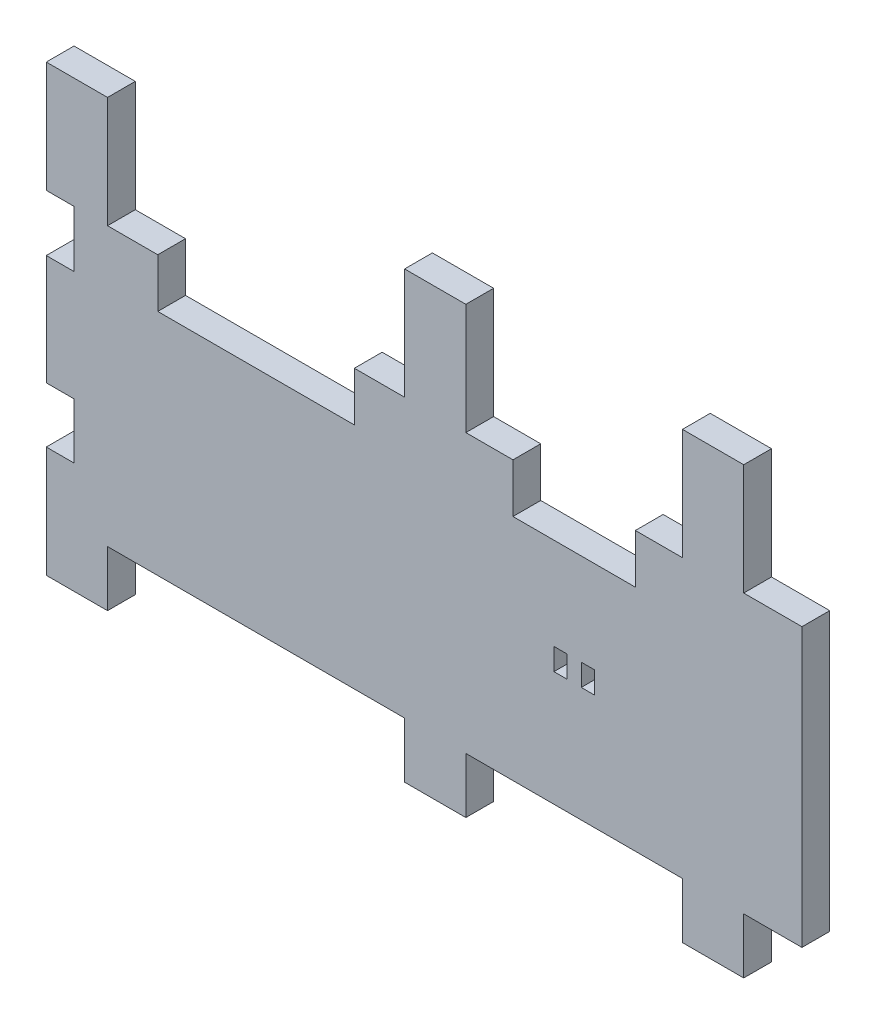
SolidWorks part; units mm, degrees
ref_plane "Front Plane" through (0, 0, 0) normal (0, 0, 1) x (1, 0, 0)
ref_plane "Top Plane" through (0, 0, 0) normal (0, 1, 0) x (1, 0, 0)
ref_plane "Right Plane" through (0, 0, 0) normal (1, 0, 0) x (0, 0, -1)
sketch "Sketch2" plane through (0, 0, 0) normal (0, 0, 1) x (1, 0, 0)
  line L1 (-88.9, -50.8) -> (88.9, -50.8)
  line L2 (-88.9, -50.8) -> (-88.9, 50.8)
  line L3 (-88.9, 50.8) -> (88.9, 50.8)
  line L4 (88.9, -50.8) -> (88.9, 50.8)
  line L5 (-88.9, -50.8) -> (88.9, 50.8) construction
  line L6 (-88.9, 50.8) -> (88.9, -50.8) construction
  point P0 (0, 0)
  dimension "D1" = 101.6
  dimension "D2" = 177.8
extrude "Boss-Extrude3" add sketch "Sketch2" along normal blind 6.35
sketch "Sketch3" plane through (0, 0, 6.35) normal (0, 0, 1) x (1, 0, 0)
  line L0 (-88.9, 50.8) -> (-82.55, 50.8)
  line L1 (-88.9, 50.8) -> (-88.9, 35.56)
  line L2 (-88.9, -50.8) -> (88.9, -50.8) construction
  line L3 (-88.9, 50.8) -> (-74.9, 50.8)
  line L4 (88.9, 50.8) -> (-88.9, 50.8) construction
  line L5 (-82.55, 50.8) -> (-76.2, 50.8)
  line L6 (-14.65, 50.8) -> (-0.65, 50.8)
  line L7 (-88.9, 50.8) -> (-88.9, 35.56)
  line L8 (-7, 50.8) -> (5.3812, 50.8)
  line L9 (-82.55, 0) -> (-82.55, 12.5042)
  line L10 (-88.9, 50.8) -> (-88.9, -50.8) construction
  line L11 (-7, 50.8) -> (-7, 25.4)
  line L12 (-88.9, 50.8) -> (-88.9, 25.4) construction
  line L13 (-82.55, 25.4) -> (-82.55, 12.5042)
  line L14 (-82.55, 25.4) -> (-74.9, 25.4)
  line L15 (56.509, 25.4) -> (56.509, 50.8)
  line L16 (56.509, 25.4) -> (70.509, 25.4)
  line L17 (56.509, 50.8) -> (70.509, 50.8)
  line L18 (70.509, 25.4) -> (70.509, 50.8)
  line L19 (70.509, 25.4) -> (88.9, 25.4) construction
  line L20 (-82.55, 50.8) -> (-14.65, 50.8) construction
  line L21 (-0.65, 50.8) -> (56.509, 50.8) construction
  line L22 (70.509, 50.8) -> (88.9, 50.8) construction
  line L23 (70.509, -50.8) -> (88.9, -50.8) construction
  line L24 (-74.9, 50.8) -> (-74.9, 25.4)
  line L25 (-88.9, -38.1) -> (-74.9, -38.1)
  line L26 (-82.55, 50.8) -> (-14.65, 50.8)
  line L27 (-88.9, -38.1) -> (-88.9, -50.8)
  line L28 (-88.9, -50.8) -> (-74.9, -50.8)
  line L29 (-74.9, -38.1) -> (-74.9, -50.8)
  line L30 (-7, -50.8) -> (-7, -38.1)
  line L31 (70.509, 50.8) -> (70.509, 25.4)
  line L32 (70.509, 25.4) -> (88.9, 25.4)
  line L33 (70.509, 25.4) -> (70.509, 50.8)
  line L34 (70.509, 50.8) -> (88.9, 50.8)
  line L35 (88.9, 25.4) -> (88.9, 50.8)
  line L36 (7, -50.8) -> (7, -38.1)
  line L37 (-0.65, -50.8) -> (7, -50.8)
  line L38 (70.509, -38.1) -> (88.9, -38.1) construction
  line L39 (-7, -38.1) -> (7, -38.1)
  line L40 (-7, -50.8) -> (-7, -38.1)
  line L41 (88.9, -38.1) -> (88.9, -50.8)
  line L42 (70.509, -50.8) -> (88.9, -50.8)
  line L43 (70.509, -38.1) -> (70.509, -50.8)
  line L44 (70.509, -38.1) -> (88.9, -38.1)
  line L45 (70.509, -50.8) -> (70.509, -38.1)
  line L46 (-7, -50.8) -> (5.3812, -50.8)
  line L47 (-88.9, -44.45) -> (-88.9, -25.4) construction
  line L48 (-7, 50.8) -> (7, 50.8)
  line L49 (-7, 50.8) -> (-7, 25.4)
  line L50 (-7, 25.4) -> (7, 25.4)
  line L51 (7, 50.8) -> (7, 25.4)
  line L52 (-7, -38.1) -> (7, -38.1)
  line L53 (70.509, -38.1) -> (70.509, -50.8)
  line L54 (56.509, -50.8) -> (70.509, -50.8)
  line L55 (56.509, -38.1) -> (70.509, -38.1)
  line L56 (56.509, -38.1) -> (56.509, -50.8)
  line L57 (-7, -38.1) -> (-7, -50.8)
  line L58 (-7, -50.8) -> (7, -50.8)
  line L59 (7, -38.1) -> (7, -50.8)
  line L60 (-74.9, -38.1) -> (-7, -38.1)
  line L61 (-74.9, -38.1) -> (-74.9, -50.8)
  line L62 (-74.9, -50.8) -> (-7, -50.8)
  line L63 (-88.9, -50.8) -> (-88.9, -38.1)
  line L64 (-88.9, -50.8) -> (-82.55, -50.8)
  line L65 (-7, -38.1) -> (-7, -50.8)
  line L66 (7, -38.1) -> (56.509, -38.1)
  line L67 (-82.55, 25.4) -> (-82.55, 50.8)
  line L68 (7, -38.1) -> (7, -50.8)
  line L69 (-88.9, 35.56) -> (-88.9, -38.1)
  line L70 (7, -50.8) -> (56.509, -50.8)
  line L72 (-88.9, 38.1) -> (-88.9, 25.4)
  line L75 (-88.9, -25.4) -> (88.9, -25.4) construction
  line L76 (-88.9, 25.4) -> (-82.55, 25.4)
  line L78 (56.509, -38.1) -> (56.509, -50.8)
  line L80 (-88.9, 35.56) -> (-88.9, 25.4)
  line L81 (-88.9, 25.4) -> (-82.55, 25.4)
  line L83 (-88.9, -38.1) -> (-88.9, -25.4)
  line L84 (-88.9, -25.4) -> (-82.4404, -25.4)
  line L85 (-82.4404, -38.1) -> (-82.4404, -25.4)
  line L86 (-82.55, 50.8) -> (-76.2, 50.8)
  line L87 (56.509, 25.4) -> (7, 25.4)
  line L88 (56.509, 25.4) -> (56.509, 50.8)
  line L90 (-88.9, 12.5042) -> (-82.55, 12.5042) construction
  line L91 (-85.725, -12.7) -> (-82.4404, -12.7) construction
  line L92 (-82.4404, -12.7) -> (-88.9, -12.7) construction
  line L93 (-82.55, 50.8) -> (-76.2, 50.8)
  line L94 (-0.65, 50.8) -> (7, 50.8)
  line L95 (56.509, 50.8) -> (7, 50.8)
  line L96 (7, 25.4) -> (7, 50.8)
  line L97 (7, 50.8) -> (7, 25.4)
  line L98 (-88.9, -34.925) -> (-82.55, -34.925) construction
  line L99 (-14.65, 50.8) -> (-7, 50.8)
  line L100 (-74.9, 50.8) -> (-7, 50.8)
  line L101 (-82.55, -34.925) -> (-82.55, 0)
  line L102 (-82.55, 0) -> (-88.9, 0)
  line L103 (-88.9, -34.925) -> (-88.9, 0)
  line L104 (-74.9, 50.8) -> (-74.9, 25.4)
  line L106 (-82.55, 12.5042) -> (-88.9, 12.5042)
  line L107 (-88.9, 38.1) -> (-88.9, 12.5042)
  line L108 (-82.4404, -12.7) -> (-88.9, -12.7)
  line L109 (-82.4404, -12.7) -> (-82.4404, -25.4)
  line L110 (-82.4404, -25.4) -> (-88.9, -25.4)
  line L111 (-88.9, -12.7) -> (-88.9, -25.4)
  line L112 (-7, 50.8) -> (-7, 25.4)
  line L113 (-74.9, 25.4) -> (-7, 25.4)
  line L114 (-7, 50.8) -> (-7, 25.4)
  line L115 (0, 0) -> (-0.65, -50.8) construction
  line L124 (-82.55, -50.8) -> (-76.2, -50.8)
  line L126 (-82.55, -50.8) -> (-76.2, -50.8)
  line L127 (-82.4404, -38.1) -> (-82.4404, -25.4)
  line L140 (-82.55, -50.8) -> (-76.2, -50.8)
  line L143 (-88.9, -50.8) -> (-82.55, -50.8)
extrude "Cut-Extrude3" cut sketch "Sketch3" against normal through all
sketch "Sketch4" plane through (0, 0, 0) normal (0, 0, -1) x (-1, 0, 0)
  line L0 (74.9, 25.4) -> (7, 25.4) construction
  line L1 (63.4188, 14.1755) -> (18.4812, 14.1755)
  line L2 (63.4188, 14.1755) -> (63.4188, 25.4)
  line L3 (63.4188, 25.4) -> (18.4812, 25.4)
  line L4 (18.4812, 14.1755) -> (18.4812, 25.4)
  line L5 (7, 25.4) -> (40.95, 25.4) construction
  line L6 (40.95, 25.4) -> (40.95, -38.1) construction
  line L7 (74.9, -38.1) -> (7, -38.1) construction
  line L8 (40.95, 25.4) -> (40.95, 14.1755) construction
  line L9 (-83.82, -38.1) -> (-83.82, 25.4)
  line L10 (-17.7684, 25.4) -> (-31.7545, 25.4)
  line L11 (-17.7684, 25.4) -> (-17.7684, 14.176)
  line L12 (-45.7406, 25.4) -> (-45.7406, 14.176)
  line L13 (-17.7684, 14.176) -> (-45.7406, 14.176)
  line L14 (-70.509, -38.1) -> (-88.9, -38.1) construction
  line L15 (-56.509, 25.4) -> (-7, 25.4) construction
  line L16 (-31.7545, -38.1) -> (-31.7545, 25.4) construction
  line L17 (-70.509, 25.4) -> (-88.9, 25.4) construction
  line L18 (-7, -38.1) -> (-56.509, -38.1) construction
  line L19 (-83.82, 25.4) -> (-88.9, 25.4)
  line L20 (-31.7545, 25.4) -> (-45.7406, 25.4)
  line L21 (-83.82, -38.1) -> (-88.9, -38.1)
  line L22 (-88.9, -38.1) -> (-88.9, 25.4) construction
  line L23 (-88.9, -38.1) -> (-88.9, 25.4)
  dimension "D1" = 44.9376
  dimension "D2" = 11.2245
  dimension "D3" = 10.7684
  dimension "D4" = 10.7684
extrude "Cut-Extrude4" cut sketch "Sketch4" against normal through all
sketch "Sketch5" plane through (0, 0, 0) normal (0, 0, -1) x (-1, 0, 0)
  line L0 (-17.7684, 14.176) -> (-17.7684, -38.1) construction
  line L1 (-7, -38.1) -> (-56.509, -38.1) construction
  line L2 (-27.1295, -11.85) -> (-27.1295, -6.85)
  line L3 (-27.1295, -11.85) -> (-30.1295, -11.85)
  line L4 (-30.1295, -11.85) -> (-30.1295, -6.85)
  line L5 (-27.1295, -6.85) -> (-30.1295, -6.85)
  line L6 (-30.1295, -11.85) -> (-33.3795, -11.85) construction
  line L7 (-33.3795, -11.85) -> (-33.3795, -6.85)
  line L8 (-33.3795, -6.85) -> (-36.3795, -6.85)
  line L9 (-36.3795, -6.85) -> (-36.3795, -11.85)
  line L10 (-36.3795, -11.85) -> (-33.3795, -11.85)
  line L11 (-31.7545, 14.176) -> (-31.7545, -11.85) construction
  line L12 (-45.7406, 14.176) -> (-17.7684, 14.176) construction
  line L13 (-31.7545, -11.85) -> (-31.7545, -3.6233) construction
  line L14 (-27.1295, -11.85) -> (-17.7684, -11.962) construction
  dimension "D1" = 9.3611
  dimension "D2" = 52.276
  dimension "D3" = 5
  dimension "D4" = 3
extrude "Cut-Extrude5" cut sketch "Sketch5" against normal through all
